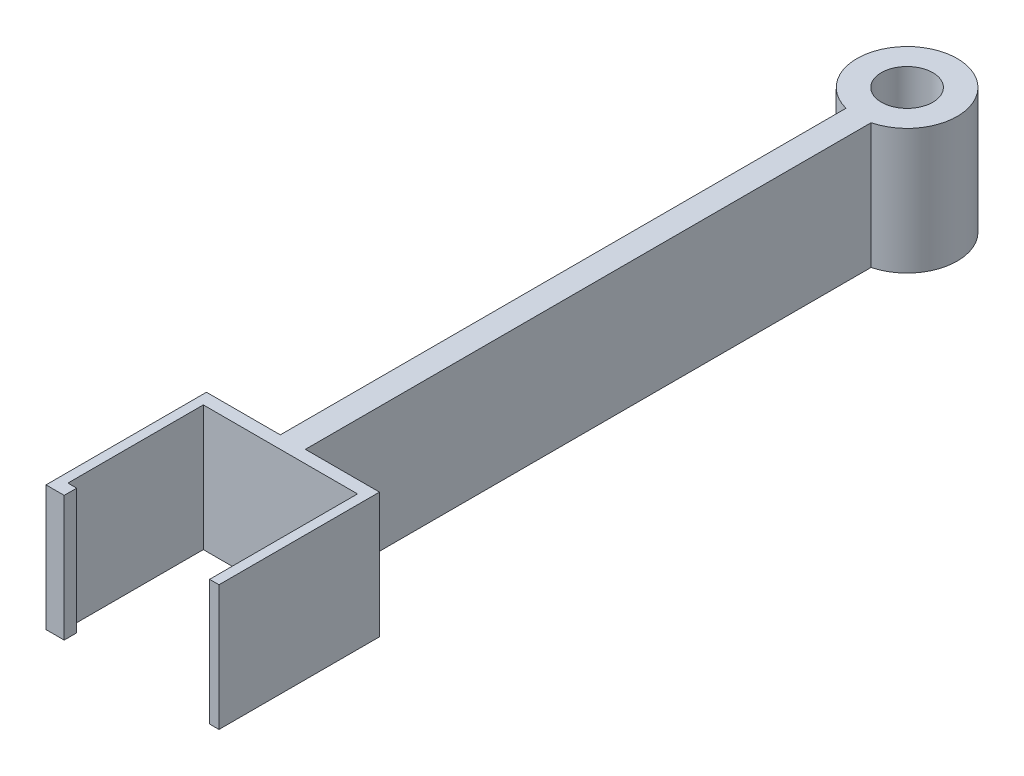
SolidWorks part; units mm, degrees
ref_plane "Front Plane" through (0, 0, 0) normal (0, 0, 1) x (1, 0, 0)
ref_plane "Top Plane" through (0, 0, 0) normal (0, 1, 0) x (1, 0, 0)
ref_plane "Right Plane" through (0, 0, 0) normal (1, 0, 0) x (0, 0, -1)
sketch "Sketch3" plane through (0, 0, 0) normal (0, 1, 0) x (1, 0, 0)
  line L1 (-6.9, 6.4) -> (6.9, 6.4)
  line L2 (-6.9, 6.4) -> (-6.9, -6.4)
  line L3 (-6.9, -6.4) -> (6.9, -6.4)
  line L4 (6.9, 6.4) -> (6.9, -6.4)
  line L5 (-6.9, 6.4) -> (6.9, -6.4) construction
  line L6 (-6.9, -6.4) -> (6.9, 6.4) construction
  point P0 (0, 0)
  dimension "D1" = 13.8
  dimension "D2" = 12.8
extrude "Boss-Extrude2" add sketch "Sketch3" along normal blind 10 contours L2 L3 L4 L1
sketch "Sketch4" plane through (0, 0, 0) normal (0, 1, 0) x (1, 0, 0)
  line L1 (-6.15, 5.4) -> (6.15, 5.4)
  line L2 (-6.15, 5.4) -> (-6.15, -5.4)
  line L3 (-6.15, -5.4) -> (6.15, -5.4)
  line L4 (6.15, 5.4) -> (6.15, -5.4)
  line L5 (-6.15, 5.4) -> (6.15, -5.4) construction
  line L6 (-6.15, -5.4) -> (6.15, 5.4) construction
  point P0 (0, 0)
  dimension "D1" = 12.3
  dimension "D2" = 10.8
extrude "Cut-Extrude1" cut sketch "Sketch4" along normal blind 10
sketch "Sketch5" plane through (0, 0, 0) normal (0, 1, 0) x (1, 0, 0)
  line L0 (6.15, -5.4) -> (6.15, 5.4) construction
  line L1 (6.15, 0) -> (-5.449, 0)
  line L2 (6.15, 0) -> (6.15, -6.4)
  line L3 (6.15, -6.4) -> (-5.449, -6.4)
  line L4 (-5.449, 0) -> (-5.449, -6.4)
  line L5 (-6.9, -6.4) -> (6.9, -6.4) construction
extrude "Cut-Extrude2" cut sketch "Sketch5" along normal blind 10 contours L1 L4 L3 L2
sketch "Sketch10" plane through (0, 0, 0) normal (0, 1, 0) x (1, 0, 0)
  line L0 (6.15, 5.4) -> (-6.15, 5.4) construction
  line L1 (-1.0095, 5.4) -> (0.9905, 5.4)
  line L2 (-1.0095, 5.4) -> (-1.0095, 55.4)
  line L3 (-1.0095, 55.4) -> (0.9905, 55.4)
  line L4 (0.9905, 5.4) -> (0.9905, 55.4)
  dimension "D1" = 2
  dimension "D2" = 50
extrude "Boss-Extrude5" add sketch "Sketch10" along normal blind 10 contours L2 L3 L4 L1
sketch "Sketch12" plane through (0, 0, 0) normal (0, 1, 0) x (1, 0, 0)
  line L0 (-1.0095, 55.4) -> (0.9905, 55.4) construction
  circle A0 centre (-0.0095, 55.4) radius 4
  dimension "D1" = 8
extrude "Boss-Extrude6" add sketch "Sketch12" along normal blind 10
sketch "Sketch13" plane through (0, 0, 0) normal (0, 1, 0) x (1, 0, 0)
  circle A0 centre (-0.0095, 55.4) radius 2.05
  dimension "D1" = 4.1
extrude "Cut-Extrude4" cut sketch "Sketch13" along normal blind 10 contours A0
